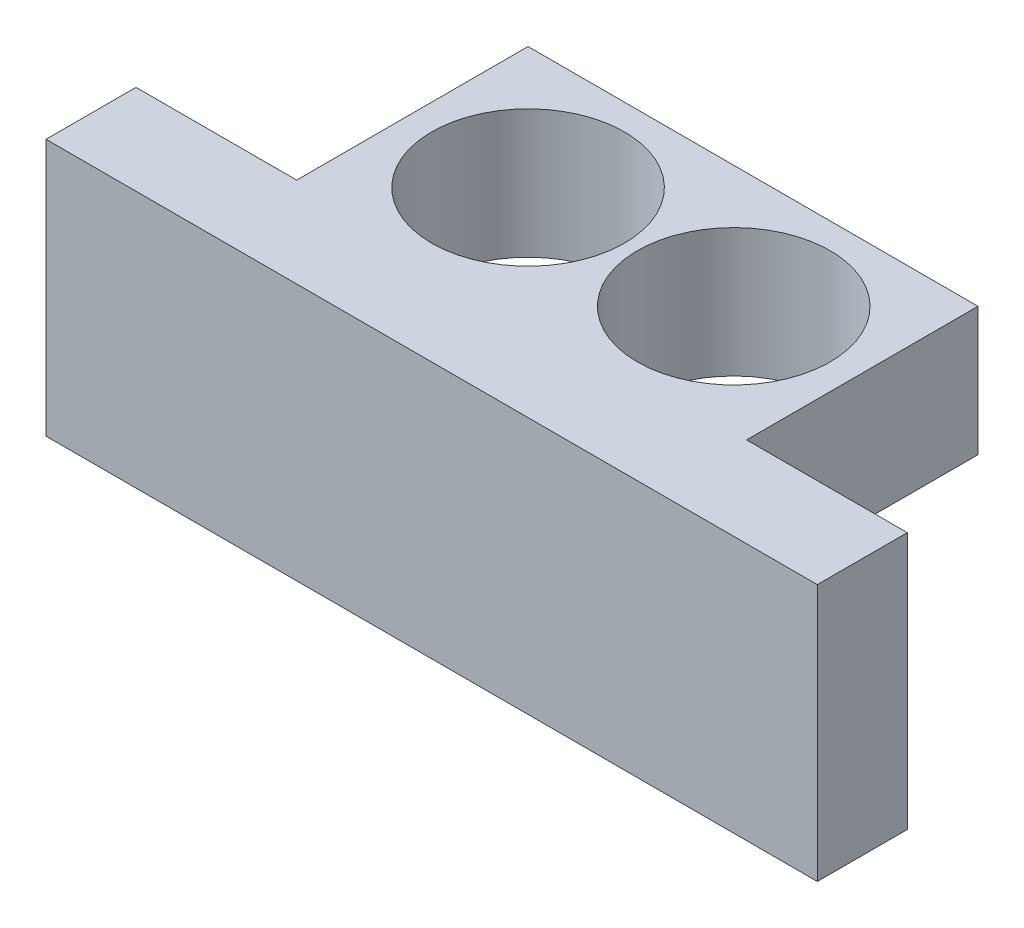
SolidWorks part; units mm, degrees
ref_plane "Front Plane" through (0, 0, 0) normal (0, 0, 1) x (1, 0, 0)
ref_plane "Top Plane" through (0, 0, 0) normal (0, 1, 0) x (1, 0, 0)
ref_plane "Right Plane" through (0, 0, 0) normal (1, 0, 0) x (0, 0, -1)
sketch "Sketch3" plane through (0, 0, 0) normal (0, 1, 0) x (1, 0, 0)
  line L1 (-15, -6.25) -> (15, -6.25)
  line L2 (-15, -6.25) -> (-15, 6.25)
  line L3 (-15, 6.25) -> (15, 6.25)
  line L4 (15, -6.25) -> (15, 6.25)
  line L5 (-15, -6.25) -> (15, 6.25) construction
  line L6 (-15, 6.25) -> (15, -6.25) construction
  point P0 (0, 0)
  dimension "D1" = 12.5
  dimension "D2" = 30
extrude "Boss-Extrude1" add sketch "Sketch3" along normal blind 10
sketch "Sketch6" plane through (0, 10, 0) normal (0, 1, 0) x (1, 0, 0)
  line L0 (-15, 6.25) -> (15, 6.25) construction
  line L2 (-15, 6.25) -> (-8.75, 6.25)
  line L3 (-15, 6.25) -> (-15, -2.75)
  line L4 (-15, -2.75) -> (-8.75, -2.75)
  line L5 (-8.75, 6.25) -> (-8.75, -2.75)
  line L6 (15, 6.25) -> (8.75, 6.25)
  line L7 (15, 6.25) -> (15, -2.75)
  line L8 (15, -2.75) -> (8.75, -2.75)
  line L9 (8.75, 6.25) -> (8.75, -2.75)
  circle A0 centre (-4, 1.5) radius 3.75
  circle A1 centre (4, 1.5) radius 3.75
  point P8 (0, 6.25)
  dimension "D3" = 7.5
  dimension "D4" = 7.5
  dimension "D5" = 4.75
  dimension "D1" = 8
  dimension "D2" = 4
  dimension "D6" = 4.75
  dimension "D7" = 4.75
  dimension "D8" = 9
  dimension "D9" = 9
extrude "Cut-Extrude2" cut sketch "Sketch6" against normal blind 10
sketch "Sketch8" plane through (0, 0, 0) normal (0, -1, 0) x (1, 0, 0)
  line L1 (-8.75, -6.25) -> (8.75, -6.25)
  line L2 (-8.75, -6.25) -> (-8.75, 2.75)
  line L3 (-8.75, 2.75) -> (8.75, 2.75)
  line L4 (8.75, -6.25) -> (8.75, 2.75)
extrude "Cut-Extrude4" cut sketch "Sketch8" against normal blind 5
